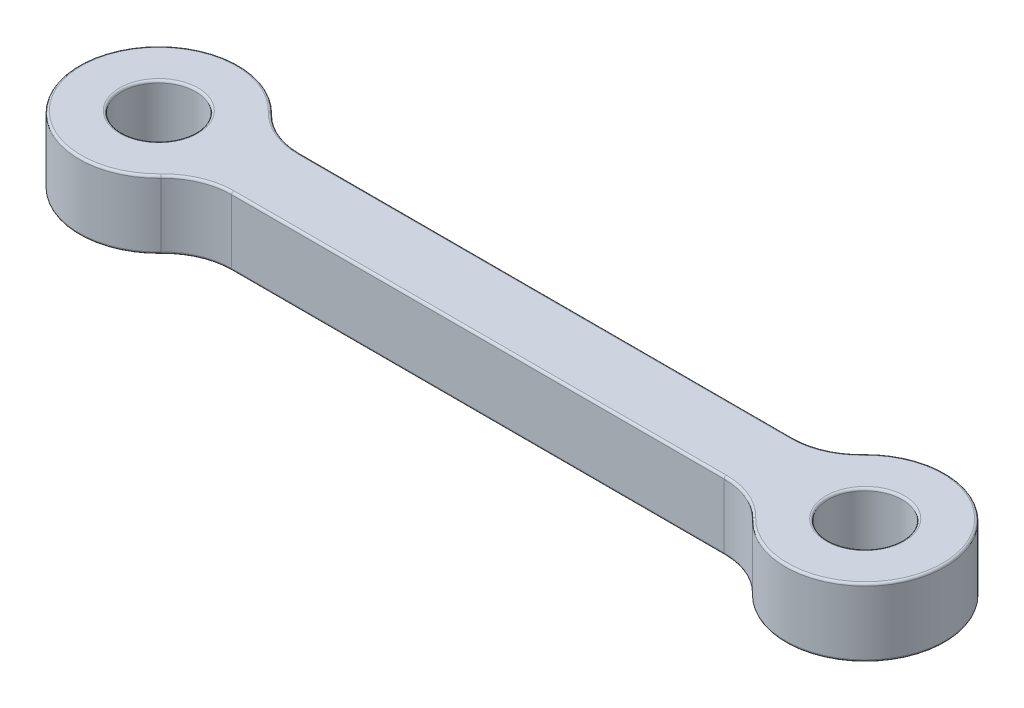
SolidWorks part; units mm, degrees
ref_plane "Front Plane" through (0, 0, 0) normal (0, 0, 1) x (1, 0, 0)
ref_plane "Top Plane" through (0, 0, 0) normal (0, 1, 0) x (1, 0, 0)
ref_plane "Right Plane" through (0, 0, 0) normal (1, 0, 0) x (0, 0, -1)
sketch "Sketch1" plane through (0, 0, 0) normal (0, 1, 0) x (1, 0, 0)
  line L0 (0, 0) -> (1.625, 0)
  line L1 (4.6904, 1.5) -> (26.3096, 1.5)
  line L2 (4.6904, -1.5) -> (26.3096, -1.5)
  line L3 (0, 1.5) -> (31, 1.5) construction
  line L5 (0, 0) -> (31, 0) construction
  line L6 (0, -1.5) -> (31, -1.5) construction
  arc A0 (2.5256, 2.4231) -> (2.5256, -2.4231) centre (0, 0) ccw
  circle A1 centre (0, 0) radius 1.625
  circle A2 centre (31, 0) radius 1.625
  arc A3 (28.4744, -2.4231) -> (28.4744, 2.4231) centre (31, 0) ccw
  arc A4 (28.4744, -2.4231) -> (26.3096, -1.5) centre (26.3096, -4.5) ccw
  arc A5 (26.3096, 1.5) -> (28.4744, 2.4231) centre (26.3096, 4.5) ccw
  arc A6 (4.6904, -1.5) -> (2.5256, -2.4231) centre (4.6904, -4.5) ccw
  arc A7 (4.6904, 1.5) -> (2.5256, 2.4231) centre (4.6904, 4.5) cw
  dimension "D1" = 7
  dimension "D2" = 3.25
  dimension "D4" = 7
  dimension "D5" = 3.25
  dimension "D8" = 3
  dimension "D3" = 31
  dimension "D6" = 1.5
  dimension "D7" = 1.5
extrude "Boss-Extrude1" add sketch "Sketch1" along normal blind 3 contours L1 A7 A0 A6 L2 A4 A3 A5 A1 A2
fillet "Fillet1" radius 0.1 20 edges at (3.5137, 0, -1.7404) (-3.5, 0, 0) (3.5137, 0, 1.7404) (15.5, 0, 1.5) (27.4863, 0, 1.7404) (34.5, 0, 0) (27.4863, 0, -1.7404) (15.5, 0, -1.5) (31, 0, 1.625) (0, 0, 1.625) (27.4863, 3, -1.7404) (34.5, 3, 0) (27.4863, 3, 1.7404) (15.5, 3, 1.5) (3.5137, 3, 1.7404) (-3.5, 3, 0) (3.5137, 3, -1.7404) (15.5, 3, -1.5) (31, 3, 1.625) (0, 3, 1.625)
scale "Ölçek1" scale about centroid uniform scaling yes scale factor 2
